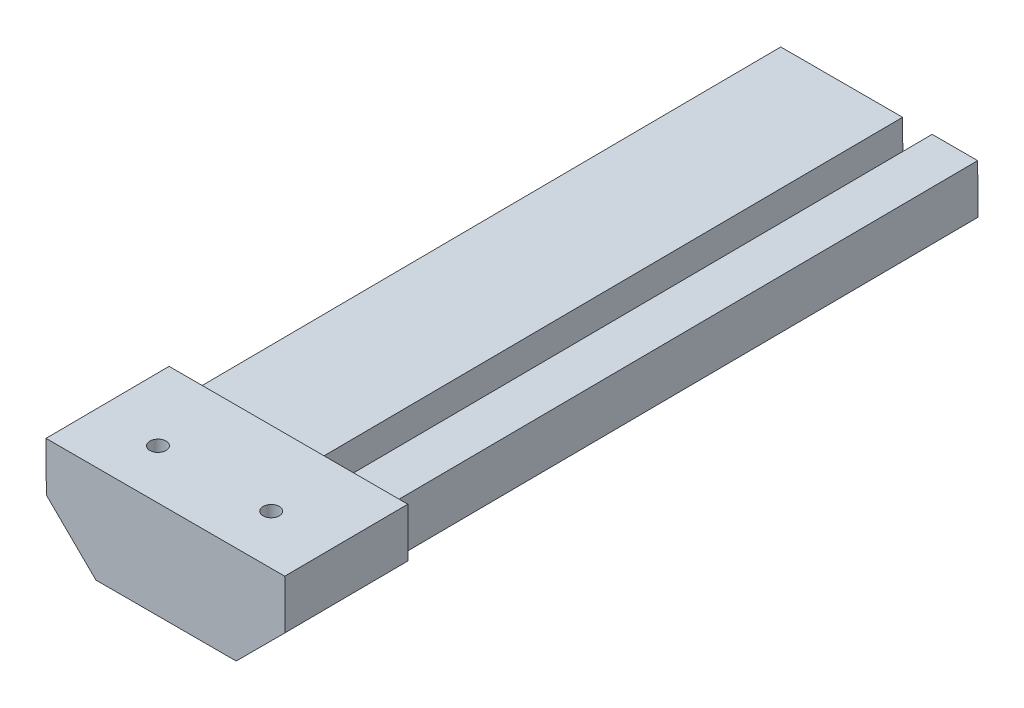
SolidWorks part; units mm, degrees
ref_plane "前视基准面" through (0, 0, 0) normal (0, 0, 1) x (1, 0, 0)
ref_plane "上视基准面" through (0, 0, 0) normal (0, 1, 0) x (1, 0, 0)
ref_plane "右视基准面" through (0, 0, 0) normal (1, 0, 0) x (0, 0, -1)
sketch "草图1" plane through (0, 51.5066, -7630.3637) normal (0, -0.0068, 1) x (1, 0, 0)
  line L0 (36.3505, 9.7351) -> (36.3505, 24.7351) construction
  line L1 (41.1004, 22.7351) -> (41.1004, 17.7351)
  line L2 (41.1004, 17.7351) -> (47.1004, 17.7351)
  line L3 (47.1004, 17.7351) -> (47.1004, 22.7351)
  line L12 (44.3505, 9.7351) -> (44.3505, 14.7351)
  line L13 (44.3505, 14.7351) -> (56.3505, 14.7351)
  line L14 (56.3505, 14.7351) -> (56.3505, 24.7351)
  line L15 (56.3505, 24.7351) -> (47.1004, 24.7351)
  line L16 (47.1004, 24.7351) -> (47.1004, 22.7351)
  line L17 (47.1004, 22.7351) -> (41.1004, 22.7351)
  line L18 (41.1004, 22.7351) -> (41.1004, 24.7351)
  line L19 (41.1004, 24.7351) -> (16.3505, 24.7351)
  line L20 (16.3505, 24.7351) -> (16.3505, 14.7351)
  line L21 (16.3505, 14.7351) -> (28.3505, 14.7351)
  line L22 (28.3505, 14.7351) -> (28.3505, 9.7351)
  line L23 (28.3505, 9.7351) -> (44.3505, 9.7351)
  line L24 (44.3505, 9.7351) -> (44.3505, 14.7351)
  line L25 (44.3505, 14.7351) -> (56.3505, 14.7351)
  line L26 (56.3505, 14.7351) -> (56.3505, 24.7351)
  line L27 (56.3505, 24.7351) -> (47.1004, 24.7351)
  line L28 (47.1004, 24.7351) -> (47.1004, 22.7351)
  line L29 (47.1004, 22.7351) -> (41.1004, 22.7351)
  line L30 (41.1004, 22.7351) -> (41.1004, 24.7351)
  line L31 (41.1004, 24.7351) -> (16.3505, 24.7351)
  line L32 (16.3505, 24.7351) -> (16.3505, 14.7351)
  line L33 (16.3505, 14.7351) -> (28.3505, 14.7351)
  line L34 (28.3505, 14.7351) -> (28.3505, 9.7351)
  line L35 (28.3505, 9.7351) -> (44.3505, 9.7351)
  line M17 (44.3505, 14.7351) -> (44.3505, 9.7351)
  line M18 (44.3505, 9.7351) -> (28.3505, 9.7351)
  line M19 (28.3505, 9.7351) -> (28.3505, 14.7351)
  line M20 (28.3505, 14.7351) -> (16.3505, 14.7351)
  line M21 (16.3505, 14.7351) -> (16.3505, 24.7351)
  line M22 (16.3505, 24.7351) -> (41.1004, 24.7351)
  line M23 (41.1004, 24.7351) -> (41.1004, 22.7351)
  line M25 (47.1004, 22.7351) -> (47.1004, 24.7351)
  line M26 (47.1004, 24.7351) -> (56.3505, 24.7351)
  line M27 (56.3505, 24.7351) -> (56.3505, 14.7351)
  line M28 (56.3505, 14.7351) -> (44.3505, 14.7351)
  dimension "D2" = 5
  dimension "D1" = 0
extrude "凸台-拉伸1" add sketch "草图1" against normal blind 120 contours L35 L0 M22 M21 M20 M19 | L0 L3 L2 L1 L31 M18 M17 M28 M27 M26 M25 M23
sketch "草图2" plane through (0, 51.5066, -7630.3637) normal (0, -0.0068, 1) x (1, 0, 0)
  line L0 (13.1005, 27.2351) -> (59.6005, 27.2351) construction
  line L1 (12.1005, 27.2351) -> (60.6005, 27.2351)
  line L2 (12.1005, 27.2351) -> (12.1005, 7.2351)
  line L3 (12.1005, 7.2351) -> (60.6005, 7.2351)
  line L4 (60.6005, 27.2351) -> (60.6005, 7.2351)
  line L5 (12.1005, 27.2351) -> (60.6005, 7.2351) construction
  line L6 (12.1005, 7.2351) -> (60.6005, 27.2351) construction
  line L7 (60.6005, 26.2351) -> (60.6005, 8.2351) construction
  line L8 (59.6005, 7.2351) -> (13.1005, 7.2351) construction
  line L9 (12.1005, 8.2351) -> (12.1005, 26.2351) construction
  point P0 (36.3505, 17.2351)
extrude "凸台-拉伸2" add sketch "草图2" along normal blind 25
sketch "草图3" plane through (0, 27.2345, 0.1838) normal (0, 1, 0.0068) x (1, 0, 0)
  line L0 (36.3505, 7630.5375) -> (36.3505, 7605.5375) construction
  line L1 (60.6005, 7605.5375) -> (12.1005, 7605.5375) construction
  line L2 (24.8505, 7615.5375) -> (47.8505, 7615.5375)
  line L3 (60.6005, 7630.5375) -> (12.1005, 7630.5375) construction
  point P8 (36.3505, 7615.5375)
  dimension "D1" = 23
  dimension "D2" = 15
hole_wizard "M4 螺纹孔1" positions "3D草图1" profile "草图4" tap size "M4" standard "GB" end condition up to next
sketch3d "3D草图1"
  point P0 (47.8505, 78.6398, -7615.1802)
  point P3 (24.8505, 78.6398, -7615.1802)
sketch "草图4" plane through (47.8505, 78.6398, -7615.1802) normal (1, 0, 0) x (0, -0.0068, 1)
  line L0 (0, 0) -> (0, 20)
  line L1 (0, 20) -> (1.65, 20)
  line L2 (1.65, 20) -> (1.65, 0)
  line L5 (1.65, 0) -> (0, 0)
  line L11 (0, -6.35) -> (0, 107.95) construction
  dimension "通孔螺纹孔钻头直径" = 3.3
  dimension "通孔螺纹孔钻头深度" = 20
cosmetic thread "孔螺蚊线1" parameters "D2"=4
cosmetic thread "孔螺蚊线2" parameters "D2"=4
sketch "草图5" plane through (0, 51.3378, -7605.3643) normal (0, -0.0068, 1) x (1, 0, 0)
  line L0 (12.1005, 27.2351) -> (12.1005, 7.2351) construction
  line L1 (12.1005, 17.2351) -> (22.1005, 7.2351)
  line L2 (60.6005, 17.2351) -> (50.6005, 7.2351)
  line L3 (60.6005, 7.2351) -> (60.6005, 27.2351) construction
  line L4 (12.1005, 7.2351) -> (60.6005, 7.2351) construction
  line L5 (12.1005, 17.2351) -> (12.1005, 7.2351)
  line L6 (12.1005, 7.2351) -> (22.1005, 7.2351)
  line L7 (50.6005, 7.2351) -> (60.6005, 7.2351)
  line L8 (60.6005, 7.2351) -> (60.6005, 17.2351)
  dimension "D1" = 45
  dimension "D2" = 45
extrude "切除-拉伸1" cut sketch "草图5" against normal up to next
